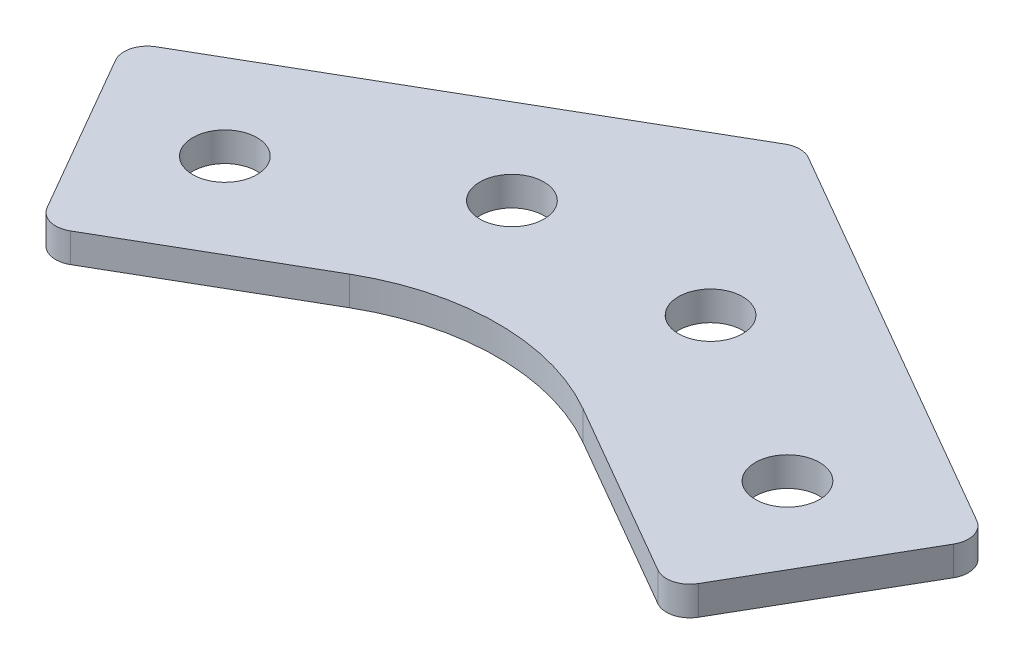
SolidWorks part; units mm, degrees
material "5052-H32"
ref_plane "Front Plane" through (0, 0, 0) normal (0, 0, 1) x (1, 0, 0)
ref_plane "Top Plane" through (0, 0, 0) normal (0, 1, 0) x (1, 0, 0)
ref_plane "Right Plane" through (0, 0, 0) normal (1, 0, 0) x (0, 0, -1)
sketch "Sketch1" plane through (0, 0, 0) normal (0, 1, 0) x (1, 0, 0)
  line L0 (-25.4, 14.6647) -> (0, 29.3294)
  line L5 (34.1504, -19.7168) -> (0, 0)
  line L6 (34.1504, -19.7168) -> (46.8504, 2.2803)
  line L7 (46.8504, 2.2803) -> (25.4, 14.6647)
  line L9 (0, 0) -> (-34.1504, -19.7168)
  line L11 (-25.4, 14.6647) -> (-46.8504, 2.2803)
  line L12 (-34.1504, -19.7168) -> (-46.8504, 2.2803)
  line L13 (0, 29.3294) -> (25.4, 14.6647)
  line L14 (-25.4, 14.6647) -> (0, 0) construction
  line L15 (25.4, 14.6647) -> (0, 0) construction
  line L16 (0, 0) -> (0, 29.3294) construction
  dimension "D1" = 25.4
  dimension "D2" = 25.4
  dimension "D5" = 120
  dimension "D3" = 39.4335
  dimension "D4" = 39.4335
extrude "Boss-Extrude1" add sketch "Sketch1" along normal blind 3.175 contours L0 L13 L7 L6 L5 L9 L12 L11
sketch "Sketch2" plane through (0, 3.175, 0) normal (0, 1, 0) x (1, 0, 0)
  line L0 (-46.8504, 2.2803) -> (-34.1504, -19.7168) construction
  line L1 (-30.6017, -3.0032) -> (-40.5004, -8.7182) construction
  line L2 (46.8504, 2.2803) -> (34.1504, -19.7168) construction
  line L3 (30.6017, -3.0032) -> (40.5004, -8.7182) construction
  circle A0 centre (-30.6017, -3.0032) radius 3.4925
  circle A1 centre (30.6017, -3.0032) radius 3.4925
  dimension "D1" = 6.985
  dimension "D2" = 11.43
sketch "Sketch7" plane through (0, 3.175, 0) normal (0, 1, 0) x (1, 0, 0)
  line L0 (-46.8504, 2.2803) -> (-34.1504, -19.7168) construction
  line L1 (-30.6017, -3.0032) -> (-40.5004, -8.7182) construction
  line L2 (46.8504, 2.2803) -> (34.1504, -19.7168) construction
  line L3 (30.6017, -3.0032) -> (40.5004, -8.7182) construction
  circle A0 centre (-30.6017, -3.0032) radius 3.4925
  circle A1 centre (30.6017, -3.0032) radius 3.4925
  dimension "D1" = 6.985
  dimension "D2" = 11.43
extrude "Cut-Extrude2" cut sketch "Sketch2" against normal blind 3.175 contours A0
pattern_linear "LPattern5" count 2 spacing 22.86 along (0.866, 0, -0.5) of "Cut-Extrude2"
extrude "Cut-Extrude3" cut sketch "Sketch7" against normal blind 3.175 contours A1
pattern_linear "LPattern6" count 2 spacing 22.86 along (-0.866, 0, -0.5) of "Cut-Extrude3"
fillet "Fillet1" radius 2.54 5 edges at (0, 1.5875, -29.3294) (46.8504, 1.5875, -2.2803) (34.1504, 1.5875, 19.7168) (-46.8504, 1.5875, -2.2803) (-34.1504, 1.5875, 19.7168)
fillet "Fillet2" radius 25.4 1 edges at (0, 1.5875, 0)
equation "\"InnerAngle\"= \"AngleCD@Assem2.SLDASM\""
equation "\"StockThickness\"= .125in"
equation "\"HoleDiameter\"= .275in"
equation "\"BarWidth\"= 1in"
equation "\"HoleSpacing\"=0.9"
equation "\"AdditionalHoleCount\"= 2"
equation "\"D1@Sketch1\"=\"BarWidth\""
equation "\"D2@Sketch1\"= \"BarWidth\""
equation "\"WingLength\"= ( \"AdditionalHoleCount\" - .275 ) * \"HoleSpacing\""
equation "\"D5@Sketch1\"=\"InnerAngle\""
equation "\"D1@Boss-Extrude1\"=\"StockThickness\""
equation "\"D1@Sketch2\"=\"HoleDiameter\""
equation "\"D2@Sketch2\"=\"HoleSpacing\"/2"
equation "\"D3@LPattern5\"=\"HoleSpacing\""
equation "\"D1@LPattern5\"=\"AdditionalHoleCount\""
equation "\"D2@Sketch7\"=\"HoleSpacing\"/2"
equation "\"D1@Sketch7\"=\"HoleDiameter\""
equation "\"D3@LPattern6\"=\"HoleSpacing\""
equation "\"D1@LPattern6\"=\"AdditionalHoleCount\""
equation "\"D3@Sketch1\"=\"WingLength\""
equation "\"D4@Sketch1\"=\"WingLength\""
